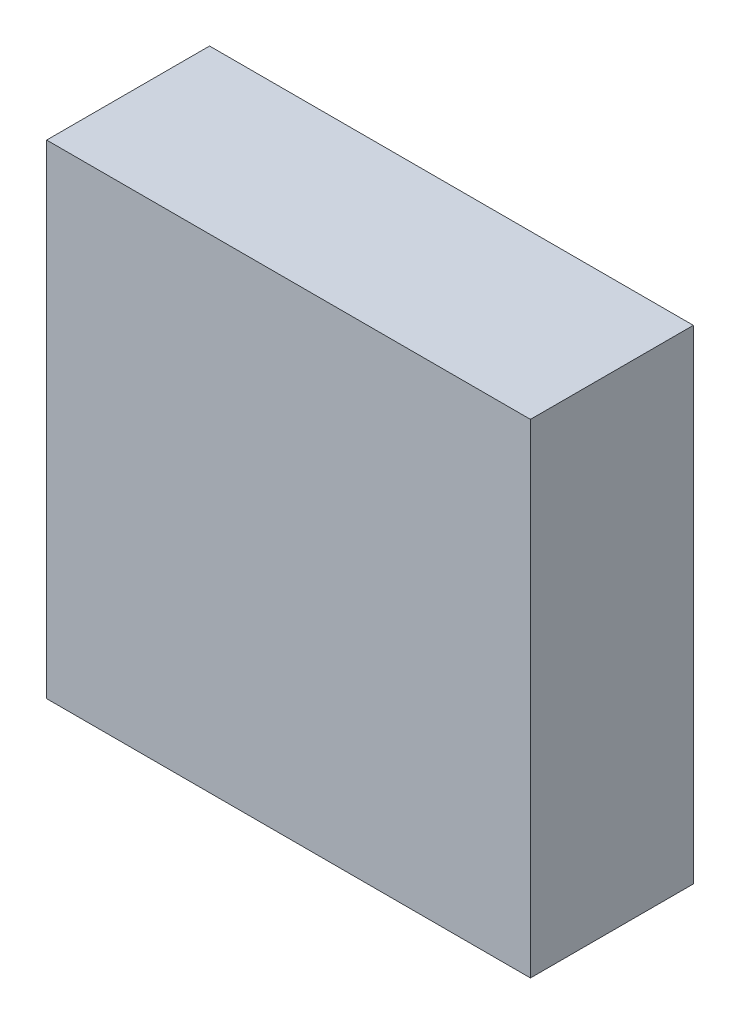
SolidWorks part; units mm, degrees
ref_plane "Front Plane" through (0, 0, 0) normal (0, 0, 1) x (1, 0, 0)
ref_plane "Top Plane" through (0, 0, 0) normal (0, 1, 0) x (1, 0, 0)
ref_plane "Right Plane" through (0, 0, 0) normal (1, 0, 0) x (0, 0, -1)
sketch "Sketch1" plane through (0, 0, 0) normal (0, 0, 1) x (1, 0, 0)
  line L1 (0, 0) -> (297, 0)
  line L2 (0, 0) -> (0, -297)
  line L3 (0, -297) -> (297, -297)
  line L4 (297, 0) -> (297, -297)
  dimension "D1" = 297
extrude "Boss-Extrude1" add sketch "Sketch1" along normal blind 100
